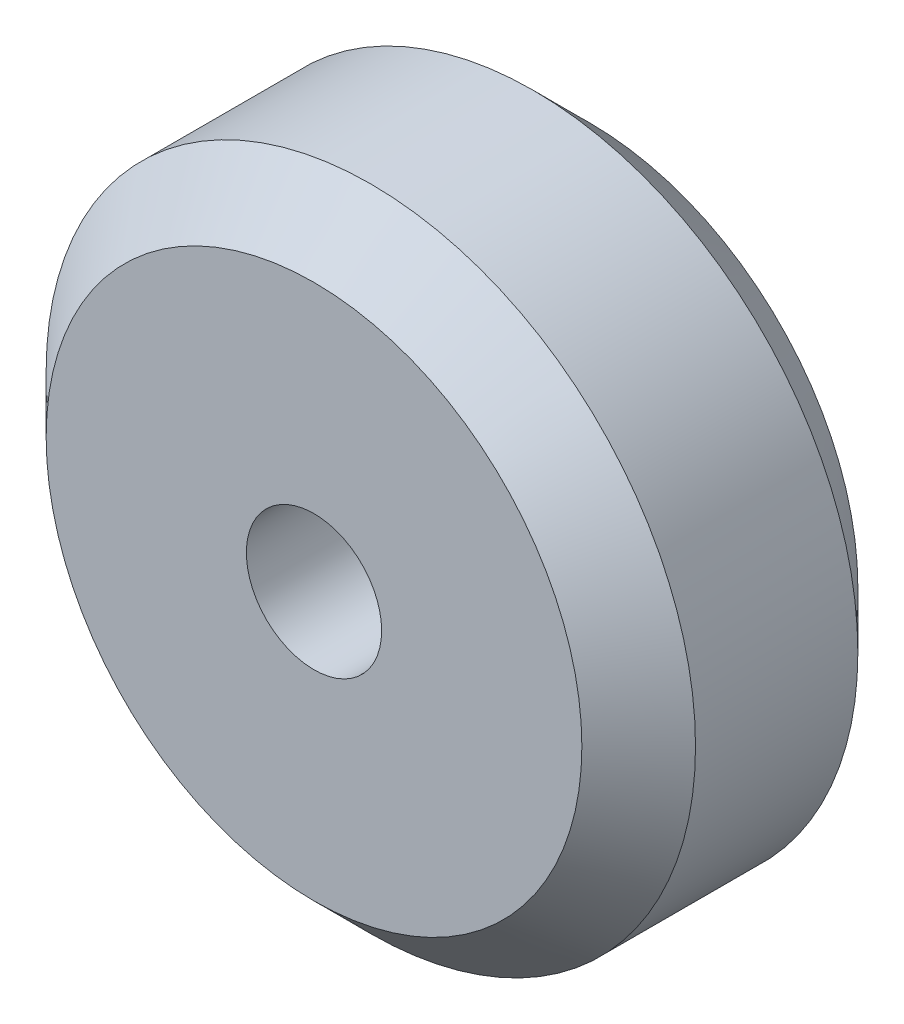
SolidWorks part; units mm, degrees
ref_plane "Front Plane" through (0, 0, 0) normal (0, 0, 1) x (1, 0, 0)
ref_plane "Top Plane" through (0, 0, 0) normal (0, 1, 0) x (1, 0, 0)
ref_plane "Right Plane" through (0, 0, 0) normal (1, 0, 0) x (0, 0, -1)
sketch "Sketch1" plane through (0, 0, 0) normal (0, 0, 1) x (1, 0, 0)
  circle A0 centre (0, 0) radius 12
  dimension "D1" = 24
extrude "Boss-Extrude1" add sketch "Sketch1" along normal blind 10.2
sketch "Sketch2" plane through (0, 0, 10.2) normal (0, 0, 1) x (1, 0, 0)
  circle A0 centre (0, 0) radius 2.5
  dimension "D1" = 5
extrude "Cut-Extrude1" cut sketch "Sketch2" against normal through all
chamfer "Chamfer1" distance 2.1 angle 45 1 edges at (12, 0, 10.2)
chamfer "Chamfer2" distance 2.1 angle 45 1 edges at (12, 0, 0)
